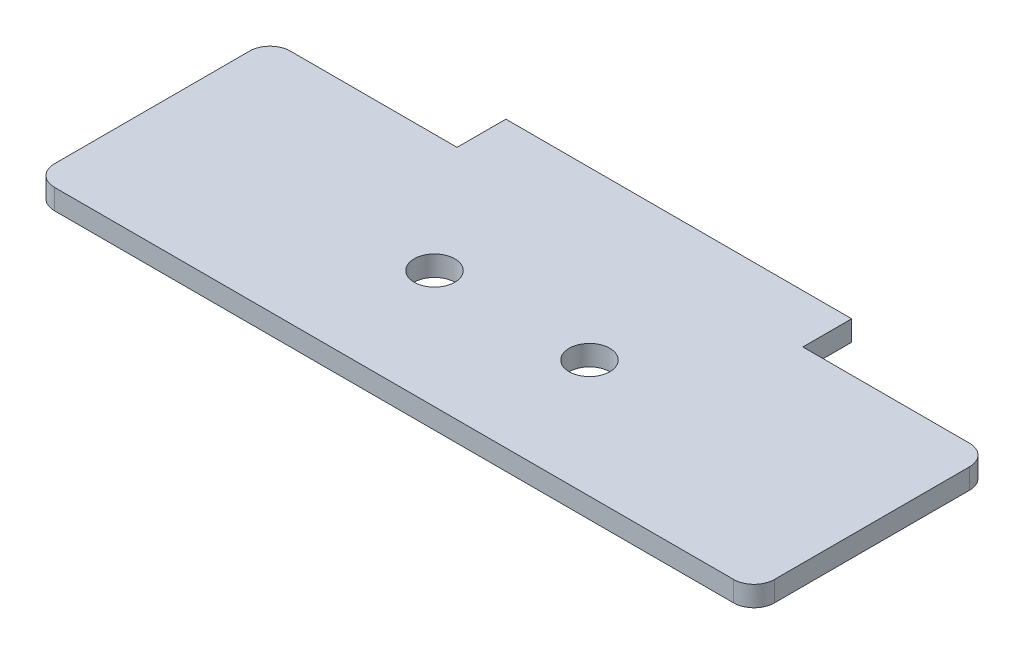
SolidWorks part; units mm, degrees
ref_plane "Front Plane" through (0, 0, 0) normal (0, 0, 1) x (1, 0, 0)
ref_plane "Top Plane" through (0, 0, 0) normal (0, 1, 0) x (1, 0, 0)
ref_plane "Right Plane" through (0, 0, 0) normal (1, 0, 0) x (0, 0, -1)
sketch "Sketch1" plane through (0, 0, 0) normal (0, 1, 0) x (1, 0, 0)
  line L0 (6.155, 2.9) -> (10.255, 2.9)
  line L1 (-6.445, 2.9) -> (-2.345, 2.9)
  line L2 (-6.945, 2.4) -> (-6.945, -2.4)
  line L3 (-6.445, -2.9) -> (10.255, -2.9)
  line L4 (10.755, 2.4) -> (10.755, -2.4)
  line L5 (-2.345, 4.1) -> (6.155, 4.1)
  line L6 (-2.345, 4.1) -> (-2.345, 2.9)
  line L8 (6.155, 4.1) -> (6.155, 2.9)
  line L9 (-6.945, 0) -> (10.755, 0) construction
  circle A1 centre (0, 0) radius 0.5
  circle A2 centre (3.81, 0) radius 0.5
  arc A4 (-6.445, 2.9) -> (-6.945, 2.4) centre (-6.445, 2.4) ccw
  arc A5 (10.255, 2.9) -> (10.755, 2.4) centre (10.255, 2.4) cw
  arc A6 (10.255, -2.9) -> (10.755, -2.4) centre (10.255, -2.4) ccw
  arc A7 (-6.945, -2.4) -> (-6.445, -2.9) centre (-6.445, -2.4) ccw
  point P18 (0, 0)
  point P19 (0, 0)
  point P20 (1.905, 0)
  point P22 (0, 0)
  point P25 (-6.945, 2.9)
  point P30 (10.755, -2.9)
  point P33 (-6.945, -2.9)
  dimension "D8" = 3.81
  dimension "D11" = 0.5
  dimension "D1" = 17.7
  dimension "D2" = 5.8
  dimension "D3" = 4.6
  dimension "D4" = 4.6
  dimension "D5" = 7
  dimension "D10" = 1.905
extrude "Boss-Extrude1" add sketch "Sketch1" along normal blind 0.5
